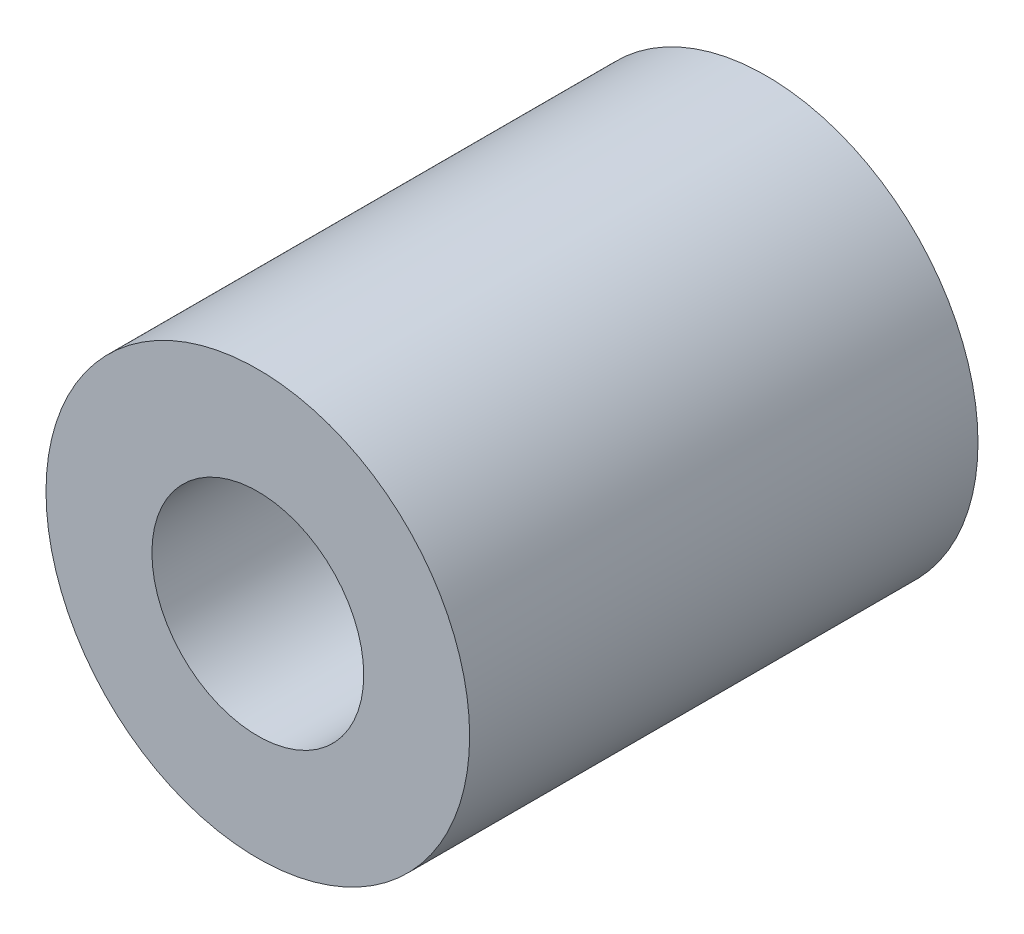
SolidWorks part; units mm, degrees
material "Латунь"
ref_plane "Спереди" through (0, 0, 0) normal (0, 0, 1) x (1, 0, 0)
ref_plane "Сверху" through (0, 0, 0) normal (0, 1, 0) x (1, 0, 0)
ref_plane "Справа" through (0, 0, 0) normal (1, 0, 0) x (0, 0, -1)
sketch "Эскиз1" plane through (0, 0, 0) normal (0, 0, 1) x (1, 0, 0)
  line L0 (0, 0) -> (0, 4) construction
  circle A0 centre (0, 1) radius 2.5 construction
  circle A3 centre (0, 1) radius 3 construction
  point P2 (0, -1.5)
  dimension "D1" = 5
  dimension "D3" = 6
  dimension "D2" = 1.5
sketch "Эскиз2" plane through (0, 0, 0) normal (0, 0, 1) x (1, 0, 0)
  circle A0 centre (0, 1) radius 2.5
extrude "Бобышка-Вытянуть1" add sketch "Эскиз2" along normal blind 6
sketch "Эскиз6" [suppressed] plane through (0, 0, 0) normal (0, 0, 1) x (1, 0, 0)
  line L1 (2.8868, 1) -> (1.4434, 3.5)
  line L2 (1.4434, 3.5) -> (-1.4434, 3.5)
  line L3 (-1.4434, 3.5) -> (-2.8868, 1)
  line L4 (-2.8868, 1) -> (-1.4434, -1.5)
  line L5 (-1.4434, -1.5) -> (1.4434, -1.5)
  line L6 (1.4434, -1.5) -> (2.8868, 1)
  circle A0 centre (0, 1) radius 2.5 construction
  circle A1 centre (0, 1) radius 2.5 construction
extrude "Бобышка-Вытянуть2" [suppressed] add sketch "Эскиз6" along normal blind 6 contours L3 L4 L5 L6 L1 L2
sketch "Эскиз7" [suppressed] plane through (0, 0, 0) normal (0, 0, 1) x (1, 0, 0)
  line L1 (3.4641, 1) -> (1.7321, 4)
  line L2 (1.7321, 4) -> (-1.7321, 4)
  line L3 (-1.7321, 4) -> (-3.4641, 1)
  line L4 (-3.4641, 1) -> (-1.7321, -2)
  line L5 (-1.7321, -2) -> (1.7321, -2)
  line L6 (1.7321, -2) -> (3.4641, 1)
  circle A0 centre (0, 1) radius 3 construction
  circle A1 centre (0, 1) radius 3 construction
extrude "Бобышка-Вытянуть3" [suppressed] add sketch "Эскиз7" along normal blind 6
sketch "Эскиз8" [suppressed] plane through (0, 0, 0) normal (0, 0, 1) x (1, 0, 0)
  circle A0 centre (0, 1) radius 3
extrude "Бобышка-Вытянуть4" [suppressed] add sketch "Эскиз8" along normal blind 6
hole_wizard "Отверстие обработанное метчиком M3x0.51" positions "Эскиз3" profile "Эскиз5" tap size "M3x0.5" standard "Ansi Metric" end condition through all
sketch "Эскиз3" plane through (0, 0, 0) normal (0, 0, 1) x (1, 0, 0)
  point P0 (0, 1)
sketch "Эскиз5" plane through (0, 1, 0) normal (1, 0, 0) x (0, 1, 0)
  line L0 (0, 0) -> (0, 6)
  line L1 (0, 6) -> (1.25, 6)
  line L2 (1.25, 6) -> (1.25, 0.4)
  line L3 (1.25, 0.4) -> (1.65, 0)
  line L5 (1.65, 0) -> (0, 0)
  line L6 (-1.25, 0.4) -> (-1.65, 0) construction
  line L11 (0, -6.35) -> (0, 107.95) construction
  dimension "Диаметр резьбы" = 2.5
  dimension "Глубина проходного сверла" = 6
  dimension "Диаметр передней зенковки" = 3.3
  dimension "Угол передней зенковки" = 90
equation "\"D3@Эскиз1\"=\"D1@Эскиз1\"+1"
